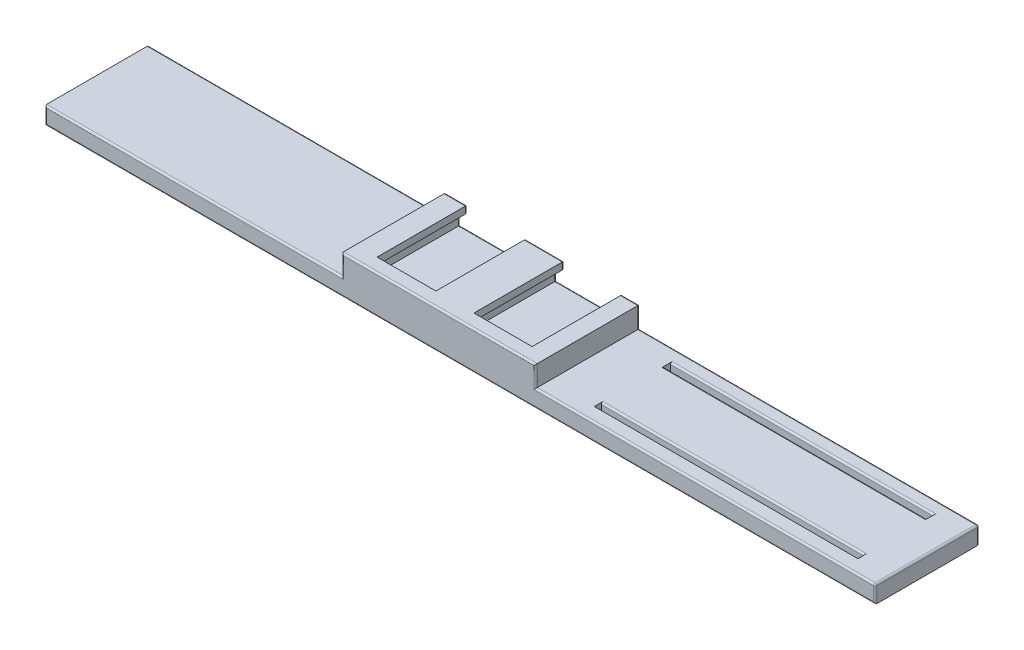
SolidWorks part; units mm, degrees
ref_plane "Front Plane" through (0, 0, 0) normal (0, 0, 1) x (1, 0, 0)
ref_plane "Top Plane" through (0, 0, 0) normal (0, 1, 0) x (1, 0, 0)
ref_plane "Right Plane" through (0, 0, 0) normal (1, 0, 0) x (0, 0, -1)
sketch "Sketch2" plane through (0, 0, 0) normal (0, 1, 0) x (1, 0, 0)
  line L0 (0, 0) -> (240, 0)
  line L1 (240, 0) -> (240, -30)
  line L2 (0, 0) -> (0, -30)
  line L3 (0, -30) -> (240, -30)
  line L4 (0, 0) -> (87.1499, 0)
extrude "Boss-Extrude1" add sketch "Sketch2" along normal blind 5 contours L2 L3 L1 L0
sketch "Sketch3" plane through (0, 5, 0) normal (0, 1, 0) x (1, 0, 0)
  line L0 (0, 0) -> (90, 0)
  line L1 (0, 0) -> (240, 0) construction
  line L2 (90, 0) -> (90, -26)
  line L3 (90, -26) -> (111, -26)
  line L4 (111, -26) -> (111, 0)
  line L5 (111, 0) -> (117.8195, 0)
  line L6 (117.8195, 0) -> (117.8195, -26)
  line L7 (117.8195, -26) -> (138.8195, -26)
  line L8 (138.8195, -26) -> (138.8195, 0)
  line L9 (138.8195, 0) -> (141.8195, 0)
  line L10 (141.8195, 0) -> (141.8195, -30)
  line L11 (0, -30) -> (240, -30) construction
  line L12 (141.8195, -30) -> (85.8195, -30)
  line L13 (85.8195, -30) -> (85.8195, 0)
  line L14 (85.8195, 0) -> (90, 0)
  line M2 (0, -30) -> (240, -30)
  line M4 (240, 0) -> (0, 0)
extrude "Boss-Extrude2" add sketch "Sketch3" along normal blind 6 contours L13 L10 L8 L7 L6 L4 L3 L2 M2 M4
sketch "Sketch4" plane through (111, 0, 0) normal (-1, 0, 0) x (0, 0, 1)
  line L0 (0, 11) -> (26, 11)
  line L1 (26, 11) -> (26, 9)
  line L2 (26, 11) -> (26, 5) construction
  line L3 (26, 9) -> (0, 9)
  line L4 (0, 11) -> (0, 5) construction
  line L5 (0, 9) -> (0, 11)
extrude "Boss-Extrude3" add sketch "Sketch4" along normal blind 2 and the other way blind 9
sketch "Sketch5" plane through (90, 0, 0) normal (1, 0, 0) x (0, 0, -1)
  line L0 (-26, 11) -> (0, 11)
  line L1 (0, 11) -> (0, 9.0012)
  line L2 (0, 11) -> (0, 5) construction
  line L3 (0, 9.0012) -> (-26, 9.0012)
  line L4 (-26, 11) -> (-26, 5) construction
  line L5 (-26, 9.0012) -> (-26, 11)
extrude "Boss-Extrude4" add sketch "Sketch5" along normal blind 2
sketch "Sketch6" plane through (138.8195, 0, 0) normal (-1, 0, 0) x (0, 0, 1)
  line L0 (26, 11) -> (26, 9)
  line L1 (26, 11) -> (26, 5) construction
  line L2 (26, 9) -> (0, 9)
  line L3 (0, 11) -> (0, 5) construction
  line L4 (0, 9) -> (0, 11)
  line L5 (0, 11) -> (26, 11)
extrude "Boss-Extrude5" add sketch "Sketch6" along normal blind 2
sketch "Sketch8" plane through (0, 5, 0) normal (0, 1, 0) x (1, 0, 0)
  line L0 (240, 0) -> (231, 0)
  line L1 (141.8195, 0) -> (240, 0) construction
  line L2 (231, 0) -> (231, -30)
  line L3 (141.8195, -30) -> (240, -30) construction
  line L4 (231, -30) -> (231, -26)
  line L5 (231, -26) -> (154.8, -26)
  line L6 (154.8, -26) -> (154.8, -24)
  line L7 (231, -24) -> (231, -26)
  line L8 (154.8, -24) -> (231, -24)
  line L9 (231, 0) -> (231, -4)
  line L10 (231, -4) -> (154.8, -4)
  line L11 (154.8, -4) -> (154.8, -6)
  line L12 (154.8, -6) -> (231, -6)
  line L13 (231, -6) -> (231, -4)
extrude "Cut-Extrude1" cut sketch "Sketch8" against normal blind 6 contours L10 L11 L12 L13 | L5 L6 L8 L7
sketch "Sketch9" plane through (0, 0, 0) normal (-1, 0, 0) x (0, 0, 1)
  line L0 (0, 5) -> (15, 5)
  line L1 (0, 5) -> (30, 5) construction
  line L2 (15, 5) -> (15, 3.5)
  line L3 (15, 3.5) -> (8.8, 3.5)
  line L4 (8.8, 3.5) -> (8.8, 1.3)
  line L5 (8.8, 1.3) -> (21.2, 1.3)
  line L6 (21.2, 1.3) -> (21.2, 3.5)
  line L7 (21.2, 3.5) -> (15, 3.5)
  line L8 (8.8, 1.3) -> (9.9961, 1.3)
  line L9 (9.9961, 1.3) -> (9.9961, 0)
  line L10 (0, 0) -> (30, 0) construction
  line L11 (9.9961, 0) -> (19.9961, 0)
  line L12 (19.9961, 0) -> (19.9961, 1.3)
  line L13 (19.9961, 1.3) -> (9.9961, 1.3)
  line M7 (0, 0) -> (30, 0)
extrude "Cut-Extrude2" cut sketch "Sketch9" against normal blind 40 contours L12 L5 L9 M7 | L6 L7 L3 L4 L5
fillet "Fillet1" radius 0.5 37 edges at (0, 2.5, 30) (42.9098, 5, 30) (85.8195, 8, 30) (85.8195, 8, 0) (113.8195, 11, 30) (141.8195, 8, 0) (141.8195, 8, 30) (190.9098, 5, 30) (240, 2.5, 30) (120, 0, 30) (100.5, 5, 0) (90, 7.0006, 0) (91, 9.0012, 0) (92, 10.0006, 0) (88.9098, 11, 0) (42.9098, 5, 0) (0, 2.5, 0) (120, 0, 0) (240, 2.5, 0) (190.9098, 5, 0) (139.3195, 11, 0) (136.8195, 10, 0) (137.8195, 9, 0) (138.8195, 7, 0) (128.3195, 5, 0) (117.8195, 7, 0) (118.9098, 9, 0) (120, 10, 0) (114.5, 11, 0) (109, 10, 0) (110, 9, 0) (111, 7, 0) (192.9, 0, 26) (192.9, 5, 24) (192.9, 5, 6) (192.9, 5, 4) (240, 5, 15)
